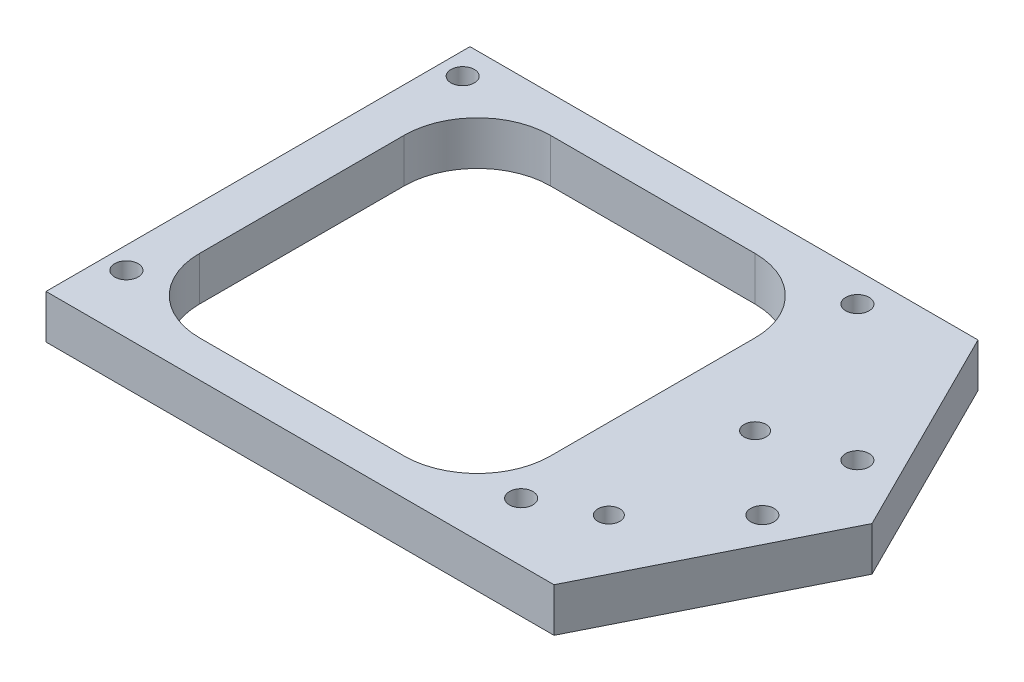
SolidWorks part; units mm, degrees
ref_plane "Front Plane" through (0, 0, 0) normal (0, 0, 1) x (1, 0, 0)
ref_plane "Top Plane" through (0, 0, 0) normal (0, 1, 0) x (1, 0, 0)
ref_plane "Right Plane" through (0, 0, 0) normal (1, 0, 0) x (0, 0, -1)
sketch "Sketch1" plane through (0, 0, 0) normal (0, 1, 0) x (1, 0, 0)
  line L0 (0, 14.5) -> (42, 14.5) construction
  line L1 (0, 0) -> (34.7484, 0)
  line L2 (0, 0) -> (0, 29)
  line L5 (42, 14.5) -> (34.7484, 29)
  line L6 (42, 14.5) -> (34.7484, 0)
  line L7 (0, 29) -> (34.7484, 29)
  dimension "D1" = 29
  dimension "D2" = 42
  dimension "D3" = 63.43
extrude "Boss-Extrude1" add sketch "Sketch1" along normal mid plane 3
sketch "Sketch2" plane through (0, 0, 0) normal (0, 1, 0) x (1, 0, 0)
  line L0 (0, 29) -> (0, 0) construction
  line L1 (3, 26.5) -> (27, 26.5)
  line L2 (3, 26.5) -> (3, 2.5)
  line L4 (27, 26.5) -> (27, 2.5)
  line L5 (0, 14.5) -> (42, 14.5) construction
  line L6 (34.7484, 29) -> (0, 29) construction
  line L7 (3, 2.5) -> (27, 2.5)
  point P14 (27, 14.5)
  point P15 (3, 14.5)
  dimension "D1" = 3
  dimension "D2" = 24
  dimension "D3" = 2.5
extrude "Cut-Extrude1" cut sketch "Sketch2" against normal through all both and the other way through all
fillet "Fillet1" radius 5 4 edges at (3, 0, -26.5) (27, 0, -26.5) (27, 0, -2.5) (3, 0, -2.5)
sketch "Sketch5" plane through (0, 1.5, 0) normal (0, 1, 0) x (1, 0, 0)
  line L0 (1.5, 27) -> (28.5, 27) construction
  line L1 (28.5, 27) -> (28.5, 4) construction
  line L2 (28.5, 4) -> (1.5, 4) construction
  line L3 (1.5, 4) -> (1.5, 27) construction
  line L4 (42, 14.5) -> (0, 14.5) construction
  line L7 (34.7484, 29) -> (0, 29) construction
  line L8 (0, 29) -> (0, 0) construction
  point P8 (37.7484, 11.25)
  point P16 (37.7484, 17.75)
  dimension "D1" = 3.25
  dimension "D2" = 2
  dimension "D3" = 1.5
  dimension "D4" = 23
  dimension "D5" = 27
  dimension "D6" = 37.7484
hole_wizard "M2x0.4 Tapped Hole1" positions "3DSketch4" profile "Sketch8" tap size "M2x0.4" standard "ANSI Metric" end condition through all
sketch3d "3DSketch4"
  point P0 (1.5, 1.5, -27)
  point P3 (28.5, 1.5, -27)
  point P6 (37.7484, 1.5, -17.75)
  point P9 (37.7484, 1.5, -11.25)
  point P12 (28.5, 1.5, -4)
  point P15 (1.5, 1.5, -4)
sketch "Sketch8" plane through (1.5, 1.5, -27) normal (1, 0, 0) x (0, 0, 1)
  line L0 (0, 0) -> (0, 3)
  line L1 (0, 3) -> (0.8, 3)
  line L2 (0.8, 3) -> (0.8, 0)
  line L5 (0.8, 0) -> (0, 0)
  line L11 (0, -6.35) -> (0, 107.95) construction
  dimension "Thru Tap Drill Dia." = 1.6
  dimension "Thru Tap Drill Depth" = 3
cosmetic thread "Hole Thread1" parameters "D2"=2
cosmetic thread "Hole Thread2" parameters "D2"=2
cosmetic thread "Hole Thread3" parameters "D2"=2
cosmetic thread "Hole Thread4" parameters "D2"=2
cosmetic thread "Hole Thread5" parameters "D2"=2
cosmetic thread "Hole Thread6" parameters "D2"=2
sketch "Sketch9" plane through (0, 1.5, 0) normal (0, 1, 0) x (1, 0, 0)
  line L3 (0, 0) -> (34.7484, 0) construction
  line L5 (0, 29) -> (0, 0) construction
  point P0 (32.5, 16)
  point P1 (32.5, 6)
  dimension "D1" = 32.5
  dimension "D2" = 16
  dimension "D3" = 6
  dimension "D4" = 32.5
hole_wizard "Ø1.5mm Dowel Hole1" positions "3DSketch5" profile "Sketch10" hole size "Ø1.5" standard "ANSI Metric" end condition through all
sketch3d "3DSketch5"
  point P0 (32.5, 1.5, -16)
  point P3 (32.5, 1.5, -6)
sketch "Sketch10" plane through (32.5, 1.5, -16) normal (1, 0, 0) x (0, 0, 1)
  line L0 (0, 0) -> (0, 3)
  line L1 (0, 3) -> (0.75, 3)
  line L2 (0.75, 3) -> (0.75, 0)
  line L5 (0.75, 0) -> (0, 0)
  line L11 (0, -6.35) -> (0, 107.95) construction
  dimension "Thru Hole Dia." = 1.5
  dimension "Thru Hole Depth" = 3
